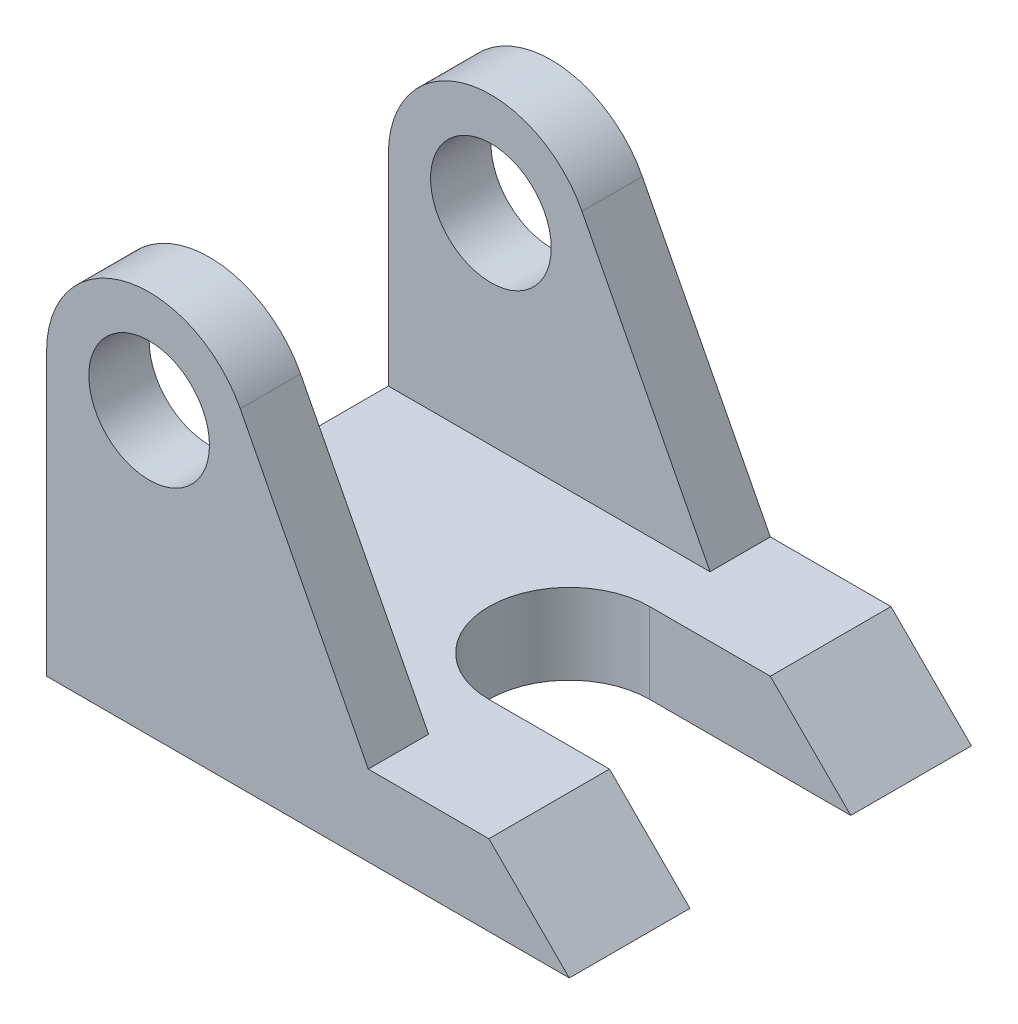
SolidWorks part; units mm, degrees
ref_plane "Front Plane" through (0, 0, 0) normal (0, 0, 1) x (1, 0, 0)
ref_plane "Top Plane" through (0, 0, 0) normal (0, 1, 0) x (1, 0, 0)
ref_plane "Right Plane" through (0, 0, 0) normal (1, 0, 0) x (0, 0, -1)
sketch "Sketch1" plane through (0, 0, 0) normal (0, 0, 1) x (1, 0, 0)
  line L0 (0, 0) -> (130, 0)
  line L1 (130, 0) -> (110, 20)
  line L2 (110, 20) -> (80, 20)
  line L3 (80, 20) -> (48.1602, 81.6946)
  line L4 (0, 0) -> (0, 70)
  arc A0 (0, 70) -> (48.1602, 81.6946) centre (25.5, 70) cw
  dimension "D1" = 130
  dimension "D2" = 20
  dimension "D3" = 20
  dimension "D4" = 70
  dimension "D5" = 25.5
  dimension "D6" = 30
extrude "Boss-Extrude1" add sketch "Sketch1" along normal mid plane 100
sketch "Sketch2" plane through (0, 20, 0) normal (0, 1, 0) x (1, 0, 0)
  line L0 (80, 50) -> (48.1602, 50) construction
  line L1 (-16.2302, 35) -> (155.707, 35)
  line L2 (-16.2302, 35) -> (-16.2302, -35)
  line L3 (-16.2302, -35) -> (155.707, -35)
  line L4 (155.707, 35) -> (155.707, -35)
  line L5 (110, -50) -> (80, -50) construction
  dimension "D1" = 15
  dimension "D2" = 15
extrude "Cut-Extrude1" cut sketch "Sketch2" along normal through all
sketch "Sketch3" plane through (0, 20, 0) normal (0, 1, 0) x (1, 0, 0)
  line L0 (80, 20) -> (153.6487, 20)
  line L1 (153.6487, 20) -> (153.6487, -20)
  line L2 (153.6487, -20) -> (80, -20)
  line L4 (130, -50) -> (130, 50) construction
  arc A0 (80, 20) -> (80, -20) centre (80, 0) ccw
  point P1 (0, 0)
  dimension "D1" = 20
  dimension "D2" = 50
extrude "Cut-Extrude2" cut sketch "Sketch3" against normal through all
hole_wizard "Ø20.0mm Dowel Hole1" positions "Sketch4" profile "Sketch6" hole size "Ø20.0" standard "ISO" end condition through all
sketch "Sketch4" plane through (0, 0, 50) normal (0, 0, 1) x (1, 0, 0)
  point P0 (25.5, 70)
sketch "Sketch6" plane through (25.5, 70, 50) normal (1, 0, 0) x (0, -1, 0)
  line L0 (0, 0) -> (0, 100)
  line L1 (0, 100) -> (15, 100)
  line L2 (15, 100) -> (15, 0)
  line L5 (15, 0) -> (0, 0)
  line L11 (0, -6.35) -> (0, 107.95) construction
  dimension "Thru Hole Dia." = 30
  dimension "Thru Hole Depth" = 100
